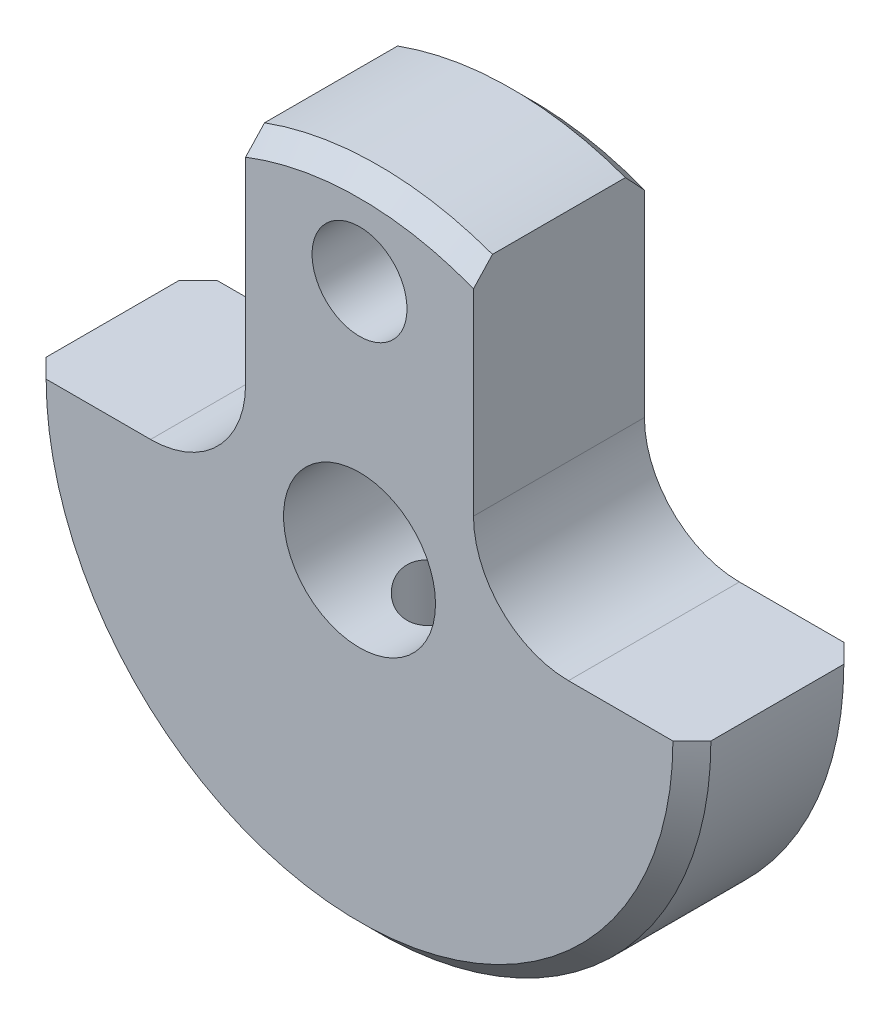
SolidWorks part; units mm, degrees
material "Gray Cast Iron"
ref_plane "Front Plane" through (0, 0, 0) normal (0, 0, 1) x (1, 0, 0)
ref_plane "Top Plane" through (0, 0, 0) normal (0, 1, 0) x (1, 0, 0)
ref_plane "Right Plane" through (0, 0, 0) normal (1, 0, 0) x (0, 0, -1)
sketch "Sketch1" plane through (0, 0, 0) normal (0, 0, 1) x (1, 0, 0)
  line L0 (0, 0) -> (0, 20.447) construction
  line L1 (6, 16.4393) -> (6, 5)
  line L2 (11, 0) -> (17.5, 0)
  line L3 (-11, 0) -> (-17.5, 0)
  line L4 (-6, 16.4393) -> (-6, 5)
  arc A0 (-17.5, 0) -> (17.5, 0) centre (0, 0) ccw
  arc A1 (11, 0) -> (6, 5) centre (11, 5) cw
  arc A2 (-11, 0) -> (-6, 5) centre (-11, 5) ccw
  arc A3 (6, 16.4393) -> (-6, 16.4393) centre (0, 0) ccw
  dimension "D1" = 35
  dimension "D3" = 5
  dimension "D2" = 6
extrude "Boss-Extrude1" add sketch "Sketch1" along normal mid plane 9
sketch "Sketch2" plane through (0, 0, 4.5) normal (0, 0, 1) x (1, 0, 0)
  circle A0 centre (0, 0) radius 4
  circle A1 centre (0, 12.7) radius 2.5
  dimension "D1" = 12.7
  dimension "D2" = 5
  dimension "D3" = 8
extrude "Cut-Extrude1" cut sketch "Sketch2" against normal blind 9
sketch "Sketch3" plane through (0, 0, 0) normal (0, 1, 0) x (1, 0, 0)
  circle A0 centre (0, 0) radius 2
extrude "Cut-Extrude2" cut sketch "Sketch3" against normal through all
chamfer "Chamfer1" distance 1 angle 45 4 edges at (0, 17.5, -4.5) (0, 17.5, 4.5) (0, -17.5, -4.5) (0, -17.5, 4.5)
